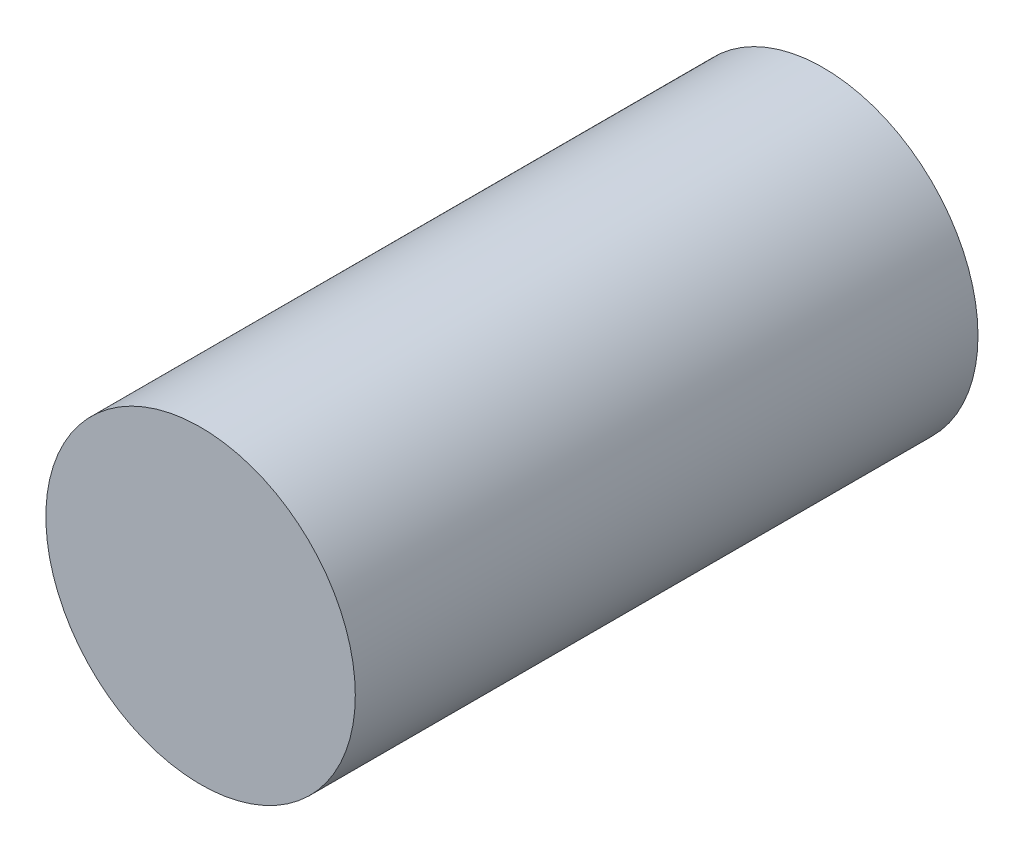
SolidWorks part; units mm, degrees
ref_plane "Front Plane" through (0, 0, 0) normal (0, 0, 1) x (1, 0, 0)
ref_plane "Top Plane" through (0, 0, 0) normal (0, 1, 0) x (1, 0, 0)
ref_plane "Right Plane" through (0, 0, 0) normal (1, 0, 0) x (0, 0, -1)
sketch "Sketch1" plane through (0, 0, 0) normal (0, 0, 1) x (1, 0, 0)
  circle A0 centre (0, 0) radius 8.2
  dimension "D1" = 16.4
extrude "Boss-Extrude1" add sketch "Sketch1" along normal blind 33
sketch "Sketch2" plane through (0, 0, 33) normal (0, 0, 1) x (1, 0, 0)
  circle A0 centre (0, 0) radius 3
  dimension "D1" = 6
extrude "Boss-Extrude2" add sketch "Sketch2" against normal blind 34
